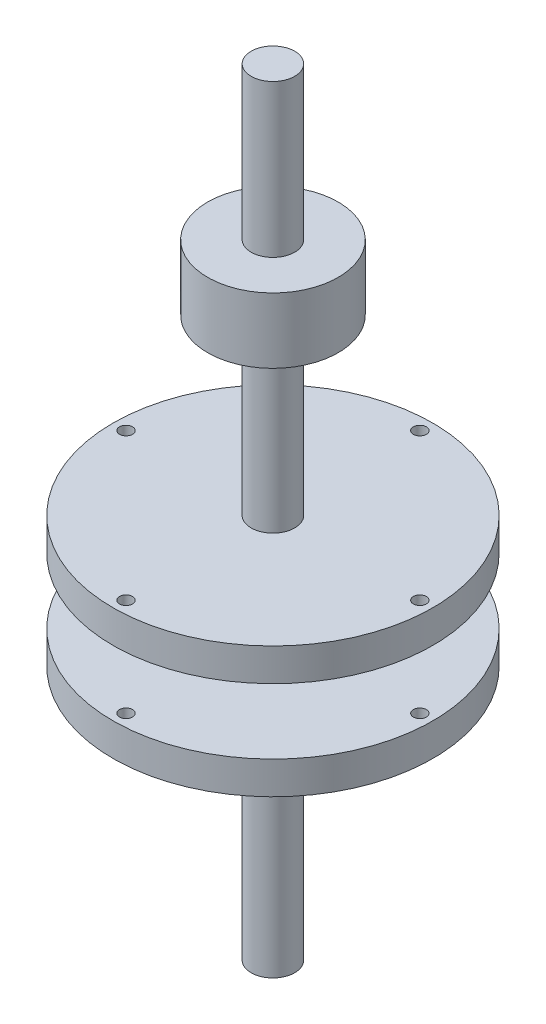
SolidWorks part; units mm, degrees
ref_plane "Front Plane" through (0, 0, 0) normal (0, 0, 1) x (1, 0, 0)
ref_plane "Top Plane" through (0, 0, 0) normal (0, 1, 0) x (1, 0, 0)
ref_plane "Right Plane" through (0, 0, 0) normal (1, 0, 0) x (0, 0, -1)
sketch "Sketch1" plane through (0, 0, 0) normal (0, 0, 1) x (1, 0, 0)
  line L0 (0, 223.9568) -> (0, -251.1973) construction
  line L1 (-10, -178.3547) -> (10, -178.3547)
  line L2 (-10, -178.3547) -> (-10, 178.3547)
  line L3 (-10, 178.3547) -> (10, 178.3547)
  line L4 (10, -178.3547) -> (10, -61.3547)
  line L5 (-10, -178.3547) -> (10, 178.3547) construction
  line L6 (-10, 178.3547) -> (10, -178.3547) construction
  line L7 (-30, 108.3547) -> (30, 108.3547)
  line L8 (-30, 108.3547) -> (-30, 78.3547)
  line L9 (-30, 78.3547) -> (30, 78.3547)
  line L10 (30, 108.3547) -> (30, 78.3547)
  line L11 (-30, 108.3547) -> (30, 78.3547) construction
  line L12 (-30, 78.3547) -> (30, 108.3547) construction
  line L13 (10, -46.3547) -> (10, -16.3547)
  line L17 (73.5, -1.3547) -> (73.5, -16.3547)
  line L18 (0, 178.3547) -> (0, -178.3547)
  line L20 (73.5, -16.3547) -> (10, -16.3547)
  line L22 (73.5, -46.3547) -> (10, -46.3547)
  line L23 (10, -16.3547) -> (10, -46.3547)
  line L24 (73.5, -46.3547) -> (73.5, -61.3547)
  line L25 (10, -1.3547) -> (10, 178.3547)
  line L26 (10, -1.3547) -> (73.5, -1.3547)
  line L27 (10, -61.3547) -> (73.5, -61.3547)
  point P0 (0, 0)
  point P6 (0, 93.3547)
  dimension "D1" = 20
  dimension "D2" = 30
  dimension "D3" = 60
  dimension "D4" = 100
  dimension "D5" = 256.7095
  dimension "D7" = 60
  dimension "D8" = 73.5
  dimension "D10" = 30
  dimension "D9" = 15
  dimension "D6" = 79.7095
revolve "Revolve3" add sketch "Sketch1" angle 360 about L0
sketch "Sketch2" plane through (0, -61.3547, 0) normal (0, -1, 0) x (1, 0, 0)
  line L1 (-67.5, 67.5) -> (67.5, 67.5) construction
  line L2 (-67.5, 67.5) -> (-67.5, -67.5) construction
  line L3 (-67.5, -67.5) -> (67.5, -67.5) construction
  line L4 (67.5, 67.5) -> (67.5, -67.5) construction
  line L5 (-67.5, 67.5) -> (67.5, -67.5) construction
  line L6 (-67.5, -67.5) -> (67.5, 67.5) construction
  circle A0 centre (67.5, 0) radius 3
  circle A1 centre (-67.5, 0) radius 3
  circle A2 centre (0, 67.5) radius 3
  circle A3 centre (0, -67.5) radius 3
  point P0 (0, 0)
  dimension "D2" = 6
  dimension "D1" = 135
extrude "Cut-Extrude1" cut sketch "Sketch2" against normal blind 80
equation "\"hatchHoleDiameter\"= 600mm"
equation "\"hullThickness\"= 120mm"
equation "\"gasketHullInterconnectWidth\"= 100mm"
equation "\"collarThickness\"= 20mm"
equation "\"hatchTunnelLength\"=200"
equation "\"oRingDiameter\"=2"
equation "\"boltPatternRadiusInterconnect\"=500"
equation "\"interconnectBoltDiameter\"=30"
equation "\"hatchShaftDiameter\"=20"
equation "\"hatchMinima\"=50"
equation "\"hullDiameter\"=2000"
equation "\"hatchMaxima\"=180"
equation "\"bushingFlatHatch\"=15"
equation "\"hingePivotDiameter\"=20"
equation "\"handleWidth\"=250"
equation "\"handleHeight\"=160"
equation "\"handleThickness\"=25"
equation "\"FrameLength\"= 2600"
equation "\"FrameMidLength\"= 1800"
equation "\"TubeOD\"= 100"
equation "\"FrameBackFlat\"= 500"
equation "\"TubeWall\"=15"
equation "\"TopMemberAngle\"=140"
equation "\"D1@Sketch1\"=\"hatchShaftDiameter\""
equation "\"HatchShaftSeatThickness\"= 30"
equation "\"D2@Sketch1\"=\"HatchShaftSeatThickness\""
equation "\"D3@Sketch1\"=\"hatchShaftDiameter\"*3"
equation "\"D5@Sketch1\"=\"hatchEdgeToTop\"+\"hatchMaxima\""
equation "\"hatchTopToDogArmCenter\"=33mm"
equation "\"dogArmSize\"=30"
equation "\"hatchPivotHeight\"=40"
equation "\"hatchPivotDistance\"=70"
equation "\"HatchORingDiameter\"=2.1"
equation "\"hatchThickness\"=50"
equation "\"hatchEdgeToTop\"=76.7095"
equation "\"D7@Sketch1\"=\"dogArmSize\"*2"
equation "\"D9@Sketch1\"=\"dogArmSize\"/2"
equation "\"D6@Sketch1\"=\"hatchTopToDogArmCenter\"+\"hatchEdgeToTop\"-\"dogArmSize\""
equation "\"D1@Sketch2\"=67.5*2"
